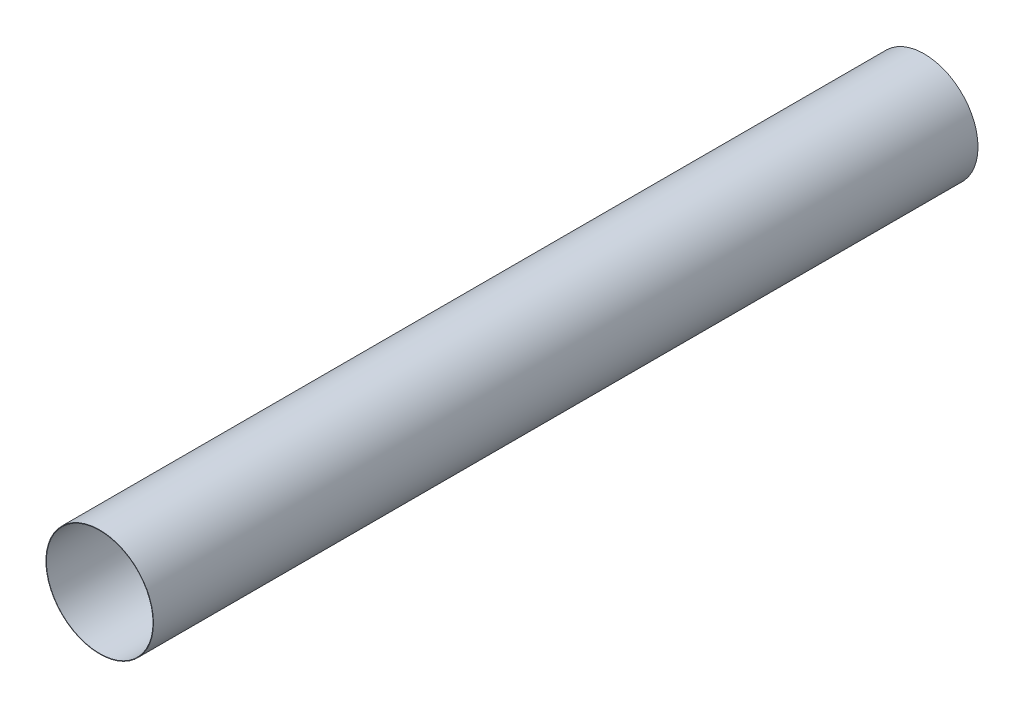
SolidWorks part; units mm, degrees
ref_plane "Front Plane" through (0, 0, 0) normal (0, 0, 1) x (1, 0, 0)
ref_plane "Top Plane" through (0, 0, 0) normal (0, 1, 0) x (1, 0, 0)
ref_plane "Right Plane" through (0, 0, 0) normal (1, 0, 0) x (0, 0, -1)
sketch "Sketch2" plane through (0, 0, 0) normal (0, 0, 1) x (1, 0, 0)
  circle A0 centre (0, 0) radius 9.525
  circle A1 centre (0, 0) radius 9.4488
  dimension "D1" = 19.05
  dimension "D2" = 0.0762
extrude "Boss-Extrude1" add sketch "Sketch2" along normal blind 146.05 contours A0
